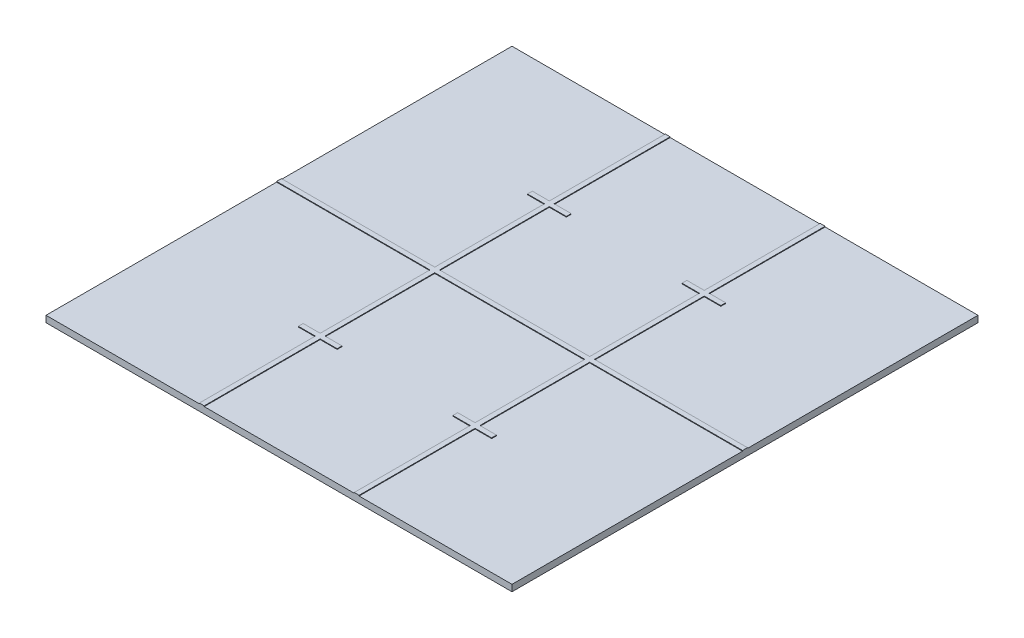
SolidWorks part; units mm, degrees
ref_plane "Front Plane" through (0, 0, 0) normal (0, 0, 1) x (1, 0, 0)
ref_plane "Top Plane" through (0, 0, 0) normal (0, 1, 0) x (1, 0, 0)
ref_plane "Right Plane" through (0, 0, 0) normal (1, 0, 0) x (0, 0, -1)
sketch "Sketch1" plane through (0, 0, 0) normal (0, 1, 0) x (1, 0, 0)
  line L3 (1765.0962, -10.3192) -> (-63.7038, -10.3192)
  line L4 (1765.0962, -10.3192) -> (1765.0962, 1818.4808)
  line L5 (1765.0962, 1818.4808) -> (-63.7038, 1818.4808)
  line L6 (-63.7038, -10.3192) -> (-63.7038, 1818.4808)
  dimension "D1" = 1828.8
  dimension "D2" = 1828.8
extrude "Boss-Extrude1" add sketch "Sketch1" along normal blind 25.4
sketch "Sketch2" plane through (0, 25.4, 0) normal (0, 1, 0) x (1, 0, 0)
  line L0 (1765.0962, 913.6058) -> (1765.0962, 894.5558)
  line L1 (1765.0962, -10.3192) -> (1765.0962, 1818.4808) construction
  line L2 (557.0667, 913.6058) -> (1145.9712, 913.6058)
  line L3 (1155.4962, 1818.4808) -> (1145.9712, 1818.4808)
  line L4 (-63.7038, 913.6058) -> (-63.7038, 894.5558)
  line L11 (1765.0962, 1818.4808) -> (-63.7038, 1818.4808) construction
  line L12 (1145.9712, 1818.4808) -> (1145.9712, 1363.2869)
  line L13 (1145.9712, -10.3192) -> (1165.0212, -10.3192)
  line L14 (-63.7038, -10.3192) -> (1765.0962, -10.3192) construction
  line L15 (1165.0212, -10.3192) -> (1165.0212, 444.8747)
  line L16 (1165.0212, 1818.4808) -> (1155.4962, 1818.4808)
  line L17 (538.0167, -10.3192) -> (557.0667, -10.3192)
  line L18 (557.0667, -10.3192) -> (557.0667, 444.8747)
  line L21 (1765.0962, 913.6058) -> (1165.0212, 913.6058)
  line L22 (-63.7038, 1818.4808) -> (-63.7038, -10.3192) construction
  line L26 (557.0667, 913.6058) -> (557.0667, 1344.2369)
  line L28 (538.0167, 894.5558) -> (538.0167, 463.9247)
  line L30 (1165.0212, 913.6058) -> (1165.0212, 1344.2369)
  line L31 (1145.9712, 894.5558) -> (1145.9712, 463.9247)
  line L32 (1165.0212, 894.5558) -> (1765.0962, 894.5558)
  line L34 (538.0167, 1818.4808) -> (557.0667, 1818.4808)
  line L37 (557.0667, 1344.2369) -> (623.7417, 1344.2369)
  line L38 (623.7417, 1344.2369) -> (623.7417, 1363.2869)
  line L40 (471.3417, 1363.2869) -> (471.3417, 1344.2369)
  line L47 (538.0167, 463.9247) -> (471.3417, 463.9247)
  line L48 (557.0667, 894.5558) -> (1145.9712, 894.5558)
  line L50 (1077.6507, 463.9247) -> (1145.9712, 463.9247)
  line L58 (1077.6507, 1363.2869) -> (1145.9712, 1363.2869)
  line L59 (557.0667, 463.9247) -> (557.0667, 894.5558)
  line L60 (538.0167, 444.8747) -> (538.0167, -10.3192)
  line L61 (1165.0212, 463.9247) -> (1165.0212, 894.5558)
  line L62 (1145.9712, 444.8747) -> (1145.9712, -10.3192)
  line L63 (1077.6507, 444.8747) -> (1145.9712, 444.8747)
  line L64 (1165.0212, 463.9247) -> (1230.0507, 463.9247)
  line L65 (471.3417, 444.8747) -> (538.0167, 444.8747)
  line L66 (557.0667, 444.8747) -> (623.7417, 444.8747)
  line L67 (1165.0212, 1363.2869) -> (1165.0212, 1818.4808)
  line L68 (538.0167, 1344.2369) -> (538.0167, 913.6058)
  line L69 (1145.9712, 1344.2369) -> (1145.9712, 913.6058)
  line L70 (1077.6507, 1344.2369) -> (1145.9712, 1344.2369)
  line L71 (1165.0212, 1363.2869) -> (1230.0507, 1363.2869)
  line L72 (538.0167, 1344.2369) -> (471.3417, 1344.2369)
  line L73 (557.0667, 1363.2869) -> (623.7417, 1363.2869)
  line L74 (557.0667, 1363.2869) -> (557.0667, 1818.4808)
  line L75 (538.0167, 913.6058) -> (-63.7038, 913.6058)
  line L76 (471.3417, 1363.2869) -> (538.0167, 1363.2869)
  line L77 (538.0167, 1818.4808) -> (538.0167, 1363.2869)
  line L78 (-63.7038, 894.5558) -> (538.0167, 894.5558)
  line L79 (623.7417, 463.9247) -> (557.0667, 463.9247)
  line L80 (471.3417, 463.9247) -> (471.3417, 444.8747)
  line L81 (623.7417, 463.9247) -> (623.7417, 444.8747)
  line L82 (1165.0212, 444.8747) -> (1230.0507, 444.8747)
  line L83 (1077.6507, 463.9247) -> (1077.6507, 444.8747)
  line L84 (1230.0507, 463.9247) -> (1230.0507, 444.8747)
  line L85 (1165.0212, 1344.2369) -> (1230.0507, 1344.2369)
  line L86 (1077.6507, 1363.2869) -> (1077.6507, 1344.2369)
  line L87 (1230.0507, 1363.2869) -> (1230.0507, 1344.2369)
  dimension "D3" = 9.525
  dimension "D4" = 9.525
extrude "Boss-Extrude2" add sketch "Sketch2" along normal blind 2.54
sketch "Sketch3" plane through (0, 25.4, 0) normal (0, 1, 0) x (1, 0, 0)
  line L2 (1765.0962, -10.3192) -> (1765.0962, 894.5558) construction
  line L3 (1765.0962, 523.0808) -> (1307.8962, 523.0808)
  line L4 (1307.8962, 523.0808) -> (1307.8962, 1285.0808)
  line L5 (1307.8962, 1285.0808) -> (1765.0962, 1285.0808)
  line L6 (1765.0962, 913.6058) -> (1765.0962, 1818.4808) construction
